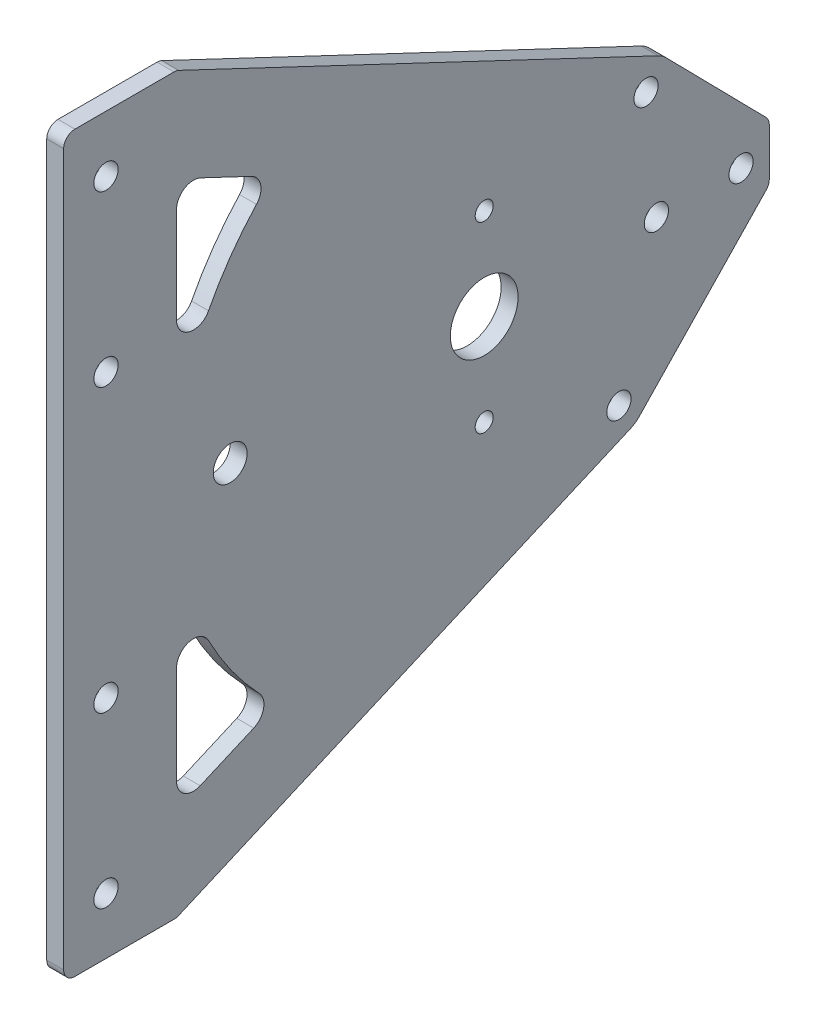
SolidWorks part; units mm, degrees
material "5052-H34"
ref_plane "正面" through (0, 0, 0) normal (0, 0, 1) x (1, 0, 0)
ref_plane "平面" through (0, 0, 0) normal (0, 1, 0) x (1, 0, 0)
ref_plane "右側面" through (0, 0, 0) normal (1, 0, 0) x (0, 0, -1)
sketch "ｽｹｯﾁ1" plane through (0, 0, 0) normal (1, 0, 0) x (0, 0, -1)
  line L0 (125, 65) -> (0, 65) construction
  line L1 (0, 0) -> (20, 0)
  line L2 (0, 0) -> (0, 130)
  line L3 (0, 130) -> (20, 130)
  line L5 (74.5, 65) -> (74.5, 59) construction
  line L10 (74.5, 65) -> (103.1703, 85.0752) construction
  line L11 (74.5, 65) -> (98.3699, 39.4026) construction
  line L12 (20, 130) -> (105.3106, 89.594)
  line L13 (20, 0) -> (100.3576, 34.8147)
  line L14 (125, 70) -> (125, 60)
  line L15 (125, 60) -> (101.9825, 35.9458)
  line L16 (125, 70) -> (106.7361, 88.5802)
  circle A0 centre (7.5, 120) radius 2.15
  circle A1 centre (7.5, 90) radius 2.15
  circle A2 centre (7.5, 40) radius 2.15
  circle A3 centre (7.5, 10) radius 2.15
  circle A4 centre (74.5, 65) radius 6
  circle A5 centre (29.5, 65) radius 3
  circle A12 centre (74.5, 65) radius 20 construction
  circle A16 centre (103.1703, 85.0752) radius 2.15
  circle A20 centre (98.3699, 39.4026) radius 2.15
  arc A25 (106.7361, 88.5802) -> (105.3106, 89.594) centre (103.1703, 85.0752) ccw
  arc A26 (100.3576, 34.8147) -> (101.9825, 35.9458) centre (98.3699, 39.4026) ccw
  arc A27 (97.5529, 65) -> (102.4657, 42.2705) centre (127.0403, 59.4778) ccw construction
  circle A28 centre (74.5, 81.215) radius 1.6
  circle A29 centre (74.5, 48.785) radius 1.6
  circle A30 centre (105, 65) radius 2.15
  circle A31 centre (120, 65) radius 2.15
  arc A33 (106.5803, 81.4184) -> (106.7361, 88.5802) centre (103.1703, 85.0752) ccw construction
  arc A34 (106.5803, 81.4184) -> (97.5529, 65) centre (127.0403, 59.4778) ccw construction
  arc A35 (101.9825, 35.9458) -> (102.4657, 42.2705) centre (98.3699, 39.4026) ccw construction
  dimension "D3" = 30
  dimension "D4" = 4.3
  dimension "D5" = 7.5
  dimension "D6" = 10
  dimension "D7" = 6
  dimension "D8" = 45
  dimension "D10" = 12
  dimension "D11" = 74.5
  dimension "D12" = 30
  dimension "D14" = 32.43
  dimension "D15" = 4.3
  dimension "D16" = 105
  dimension "D17" = 40
  dimension "D18" = 15
  dimension "D20" = 10
  dimension "D23" = 47
  dimension "D24" = 4.3
  dimension "D26" = 5
  dimension "D9" = 10
  dimension "D13" = 3.2
  dimension "D1" = 130
  dimension "D19" = 20
  dimension "D21" = 20
  dimension "D22" = 35
  dimension "D25" = 35
extrude "ﾎﾞｽ - 押し出し1" add sketch "ｽｹｯﾁ1" along normal blind 3
sketch "ｽｹｯﾁ2" plane through (3, 0, 0) normal (1, 0, 0) x (0, 0, -1)
  line L0 (20, 113.4026) -> (20, 72.3993)
  line L14 (98.8898, 76.0376) -> (13.5793, 116.4437)
  line L15 (37.0834, 105.3113) -> (20, 113.4026)
  line L16 (98.8898, 76.0376) -> (37.0834, 105.3113) construction
  line L17 (14.0369, 13.7638) -> (94.3945, 48.5785)
  line L18 (20, 16.3473) -> (37.7821, 24.0513)
  line L19 (37.7821, 24.0513) -> (94.3945, 48.5785) construction
  line L20 (20, 72.3993) -> (20, 57.6007) construction
  line L21 (20, 57.6007) -> (20, 16.3473)
  line L22 (20, 130) -> (20, 113.4026) construction
  line L23 (20, 113.4026) -> (13.5793, 116.4437) construction
  line L24 (20, 16.3473) -> (20, 0) construction
  line L25 (14.0369, 13.7638) -> (20, 16.3473) construction
  arc A0 (37.0834, 105.3113) -> (20, 72.3993) centre (74.5, 65) ccw
  arc A1 (37.7821, 24.0513) -> (37.0834, 105.3113) centre (74.5, 65) ccw construction
  arc A2 (20, 72.3993) -> (20, 57.6007) centre (74.5, 65) ccw construction
  arc A3 (20, 57.6007) -> (37.7821, 24.0513) centre (74.5, 65) ccw
  dimension "D1" = 110
  dimension "D2" = 15
  dimension "D3" = 15
extrude "ｶｯﾄ - 押し出し1" cut sketch "ｽｹｯﾁ2" against normal up to surface (3 mm away) up to face at (0, 63.8916, -70.4488)
fillet "ﾌｨﾚｯﾄ1" radius 2 6 edges at (1.5, 0, 0) (1.5, 130, 0) (1.5, 0, -20) (1.5, 130, -20) (1.5, 60, -125) (1.5, 70, -125)
fillet "ﾌｨﾚｯﾄ2" radius 3 6 edges at (1.5, 72.3993, -20) (1.5, 113.4026, -20) (1.5, 105.3113, -37.0834) (1.5, 16.3473, -20) (1.5, 24.0513, -37.7821) (1.5, 57.6007, -20)
